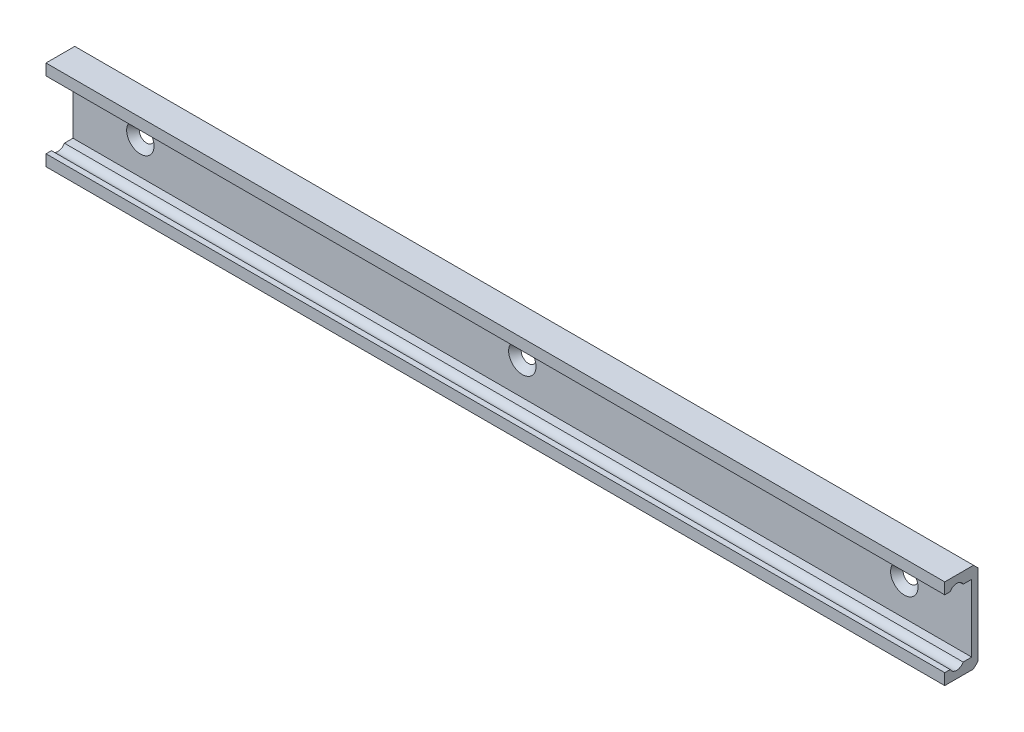
SolidWorks part; units mm, degrees
ref_plane "Front Plane" through (0, 0, 0) normal (0, 0, 1) x (1, 0, 0)
ref_plane "Top Plane" through (0, 0, 0) normal (0, 1, 0) x (1, 0, 0)
ref_plane "Right Plane" through (0, 0, 0) normal (1, 0, 0) x (0, 0, -1)
ref_plane "Plane1" through (-15, 0, 0) normal (1, 0, 0) x (0, 0, -1)
ref_plane "STROKE" through (-135, 0, 0) normal (1, 0, 0) x (0, 0, -1)
sketch "Sketch1" plane through (-15, 0, 0) normal (1, 0, 0) x (0, 0, -1)
  line L0 (-7.4, -7.5) -> (-7.4, -10)
  line L1 (-7.4, 10) -> (0, 10)
  line L2 (-7.4, 10) -> (-7.4, 7.5)
  line L3 (-7.4, -10) -> (0, -10)
  line L4 (0, 10) -> (0, -10)
  line L5 (-7.4, 7.5) -> (-6.1916, 7.5)
  line L6 (0, 0) -> (-4.75, 0) construction
  line L7 (-7.4, -7.5) -> (-6.1916, -7.5)
  line L8 (-1.4, 7.5) -> (-1.4, -7.5)
  line L9 (-4.75, 6.75) -> (-4.75, -6.75) construction
  line L10 (-3.3084, 7.5) -> (-1.4, 7.5)
  line L11 (-3.3084, -7.5) -> (-1.4, -7.5)
  arc A0 (-3.3084, 7.5) -> (-6.1916, 7.5) centre (-4.75, 6.75) ccw
  arc A1 (-6.1916, -7.5) -> (-3.3084, -7.5) centre (-4.75, -6.75) ccw
  dimension "MSM_4" = 3.25
  dimension "MSM_2" = 7.4
  dimension "MSM_7" = 1.4
  dimension "MSM_3" = 2.5
  dimension "MSM_5" = 4.75
  dimension "MSM_6" = 13.5
extrude "Boss-Extrude1" add sketch "Sketch1" along normal blind 200
fillet "Fillet1" [suppressed] radius 1.5
fillet "Fillet2" [suppressed] radius 0.2
fillet "Fillet3" [suppressed] radius 0.35
chamfer "Chamfer1" distance 1 2 edges at (85, -10, 0) (85, 10, 0)
sketch "Sketch2" plane through (0, 0, 0) normal (1, 0, 0) x (0, 0, -1)
  line L0 (0, 0) -> (-1.4, 0) construction
  line L1 (-1.4, 3.05) -> (0, 1.65)
  line L2 (0, -9) -> (0, 9) construction
  line L3 (0, 1.65) -> (0, 0)
  line L4 (0, 0) -> (-1.4, 0)
  line L5 (-1.4, 0) -> (-1.4, 3.05)
  line L6 (-1.4, 7.5) -> (-1.4, -7.5) construction
  dimension "FIX_6" = 45
  dimension "MSM_10" = 6.1
revolve "Cut-Revolve1" cut sketch "Sketch2" angle 360 about L0
pattern_linear "LPattern1" count 2 spacing 85 along (1, 0, 0) of "Cut-Revolve1"
pattern_linear "LPattern2" count 2 spacing 170 along (1, 0, 0) of "Cut-Revolve1"
equation "\"Fillet2\" = IIF ( \"MSM_1\" = 20 , \"suppressed\" , \"unsuppressed\" )"
equation "\"Fillet3\" = IIF ( \"MSM_1\" = 20 , \"suppressed\" , \"unsuppressed\" )"
equation "\"LPattern1\"= IIF ( \"MSM_8\" < 200 , \"suppressed\" , \"unsuppressed\" )"
equation "\"Fillet1\" = IIF ( \"MSM_1\" = 20 , \"suppressed\" , \"unsuppressed\" )"
equation "\"Chamfer1\"= IIF ( \"MSM_1\" = 20 , \"unsuppressed\" , \"suppressed\" )"
